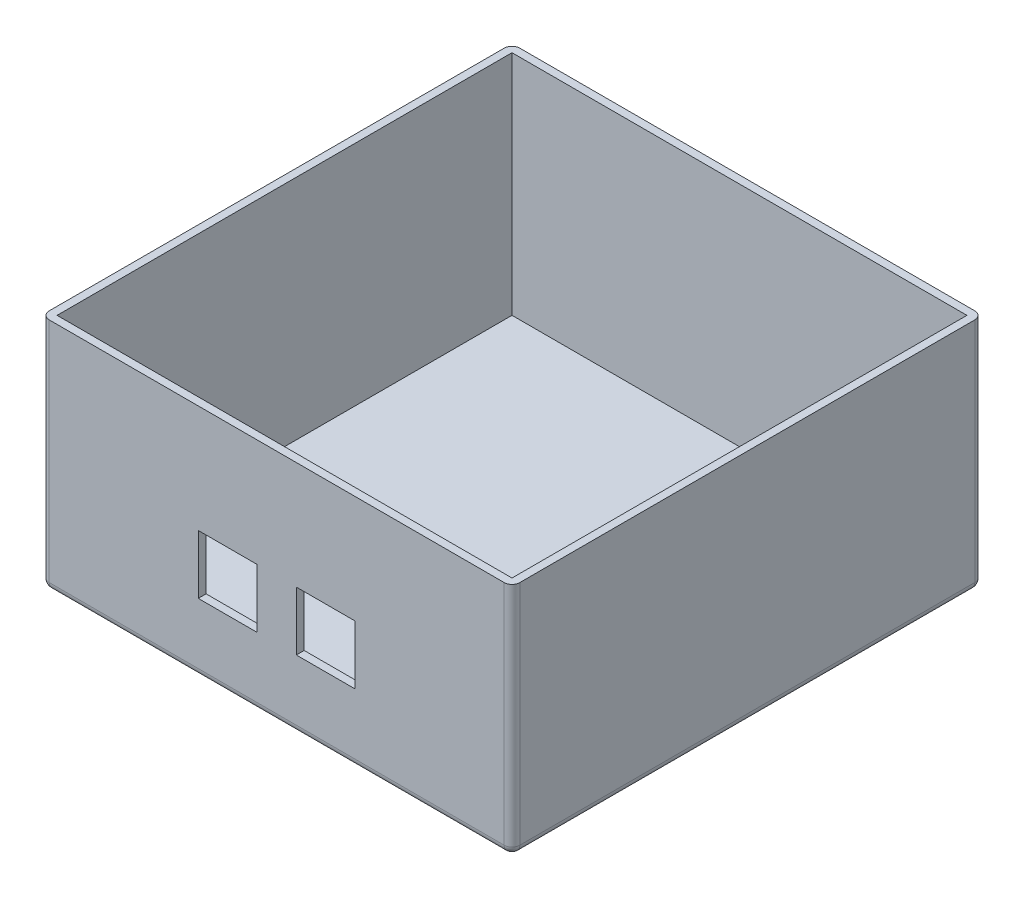
SolidWorks part; units mm, degrees
ref_plane "Front Plane" through (0, 0, 0) normal (0, 0, 1) x (1, 0, 0)
ref_plane "Top Plane" through (0, 0, 0) normal (0, 1, 0) x (1, 0, 0)
ref_plane "Right Plane" through (0, 0, 0) normal (1, 0, 0) x (0, 0, -1)
sketch "Sketch1" plane through (0, 0, 0) normal (0, 1, 0) x (1, 0, 0)
  line L1 (-60, -60) -> (60, -60)
  line L2 (-60, -60) -> (-60, 60)
  line L3 (-60, 60) -> (60, 60)
  line L4 (60, -60) -> (60, 60)
  line L5 (-60, -60) -> (60, 60) construction
  line L6 (-60, 60) -> (60, -60) construction
  point P0 (0, 0)
  dimension "D1" = 120
  dimension "D2" = 120
extrude "Boss-Extrude1" add sketch "Sketch1" along normal blind 60
shell "Shell1" thickness 2
fillet "Fillet1" radius 2 8 edges at (0, 0, -60) (60, 0, 0) (0, 0, 60) (-60, 0, 0) (-60, 30, -60) (60, 30, -60) (60, 30, 60) (-60, 30, 60)
sketch "Sketch2" plane through (0, 0, 60) normal (0, 0, 1) x (1, 0, 0)
  line L0 (-5, 17.5) -> (5, 17.5) construction
  line L1 (-20, 17.5) -> (-5, 17.5)
  line L2 (-20, 17.5) -> (-20, 32.5)
  line L3 (-20, 32.5) -> (-5, 32.5)
  line L4 (-5, 17.5) -> (-5, 32.5)
  line L5 (-20, 17.5) -> (-5, 32.5) construction
  line L6 (-20, 32.5) -> (-5, 17.5) construction
  line L7 (5, 17.5) -> (20, 17.5)
  line L8 (5, 17.5) -> (5, 32.5)
  line L9 (5, 32.5) -> (20, 32.5)
  line L10 (20, 17.5) -> (20, 32.5)
  line L11 (5, 17.5) -> (20, 32.5) construction
  line L12 (5, 32.5) -> (20, 17.5) construction
  point P0 (-12.5, 25)
  point P5 (12.5, 25)
  point P10 (0, 17.5)
  point P11 (0, 0)
  dimension "D1" = 15
  dimension "D2" = 15
  dimension "D3" = 25
  dimension "D4" = 15
  dimension "D6" = 10
extrude "Cut-Extrude1" cut sketch "Sketch2" against normal up to next
